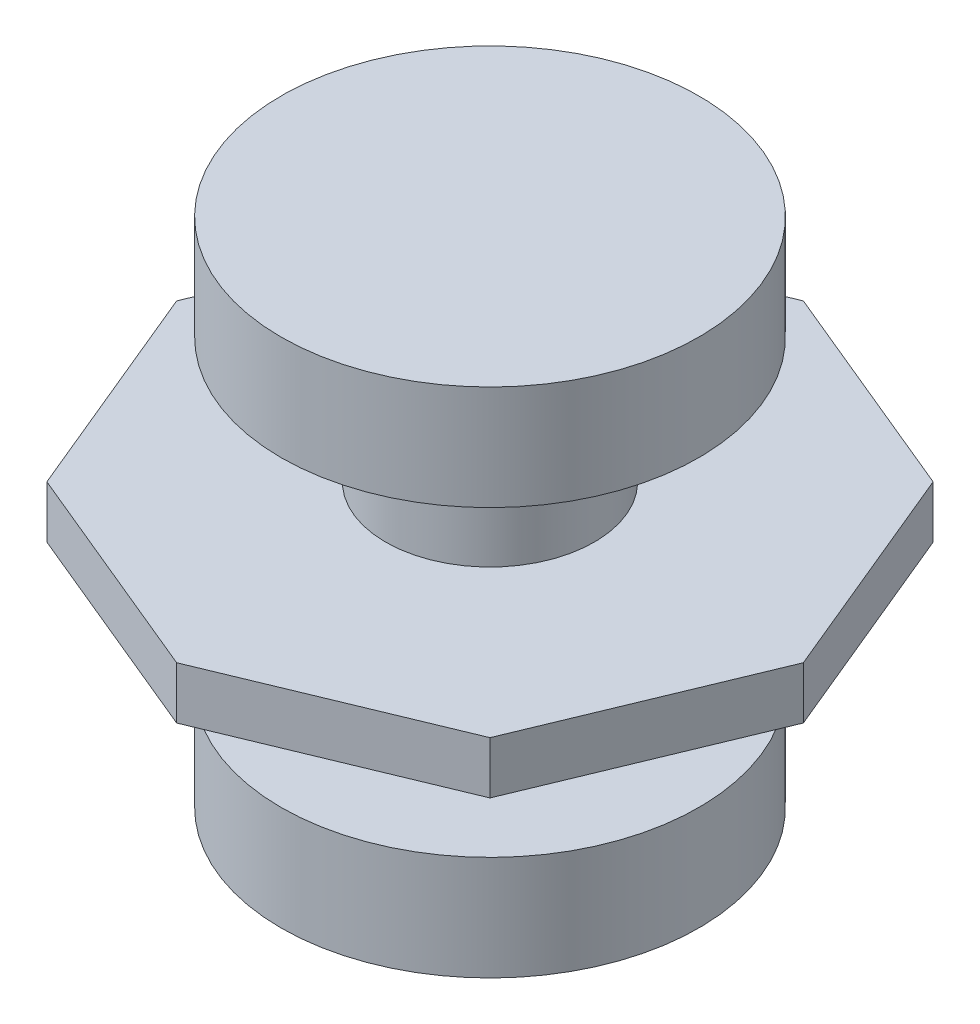
SolidWorks part; units mm, degrees
ref_plane "Front Plane" through (0, 0, 0) normal (0, 0, 1) x (1, 0, 0)
ref_plane "Top Plane" through (0, 0, 0) normal (0, 1, 0) x (1, 0, 0)
ref_plane "Right Plane" through (0, 0, 0) normal (1, 0, 0) x (0, 0, -1)
sketch "Sketch2" plane through (0, 0, 0) normal (0, 1, 0) x (1, 0, 0)
  circle A0 centre (0, 0) radius 20
extrude "Boss-Extrude1" add sketch "Sketch2" along normal blind 10
sketch "Sketch3" plane through (0, 10, 0) normal (0, 1, 0) x (1, 0, 0)
  circle A0 centre (0, 0) radius 10
extrude "Boss-Extrude2" add sketch "Sketch3" along normal blind 12 contours A0
sketch "Sketch4" plane through (0, 22, 0) normal (0, 1, 0) x (1, 0, 0)
  line L1 (30, 0) -> (21.2132, 21.2132)
  line L2 (21.2132, 21.2132) -> (0, 30)
  line L3 (0, 30) -> (-21.2132, 21.2132)
  line L4 (-21.2132, 21.2132) -> (-30, 0)
  line L5 (-30, 0) -> (-21.2132, -21.2132)
  line L6 (-21.2132, -21.2132) -> (0, -30)
  line L7 (0, -30) -> (21.2132, -21.2132)
  line L8 (21.2132, -21.2132) -> (30, 0)
  circle A0 centre (0, 0) radius 27.7164 construction
  dimension "D1" = 30
extrude "Boss-Extrude3" add sketch "Sketch4" along normal blind 5
sketch "Sketch5" plane through (0, 27, 0) normal (0, 1, 0) x (1, 0, 0)
  circle A0 centre (0, 0) radius 10
extrude "Boss-Extrude4" add sketch "Sketch5" along normal blind 12 contours A0
sketch "Sketch6" plane through (0, 39, 0) normal (0, 1, 0) x (1, 0, 0)
  circle A0 centre (0, 0) radius 20
extrude "Boss-Extrude5" add sketch "Sketch6" along normal blind 10 contours A0
